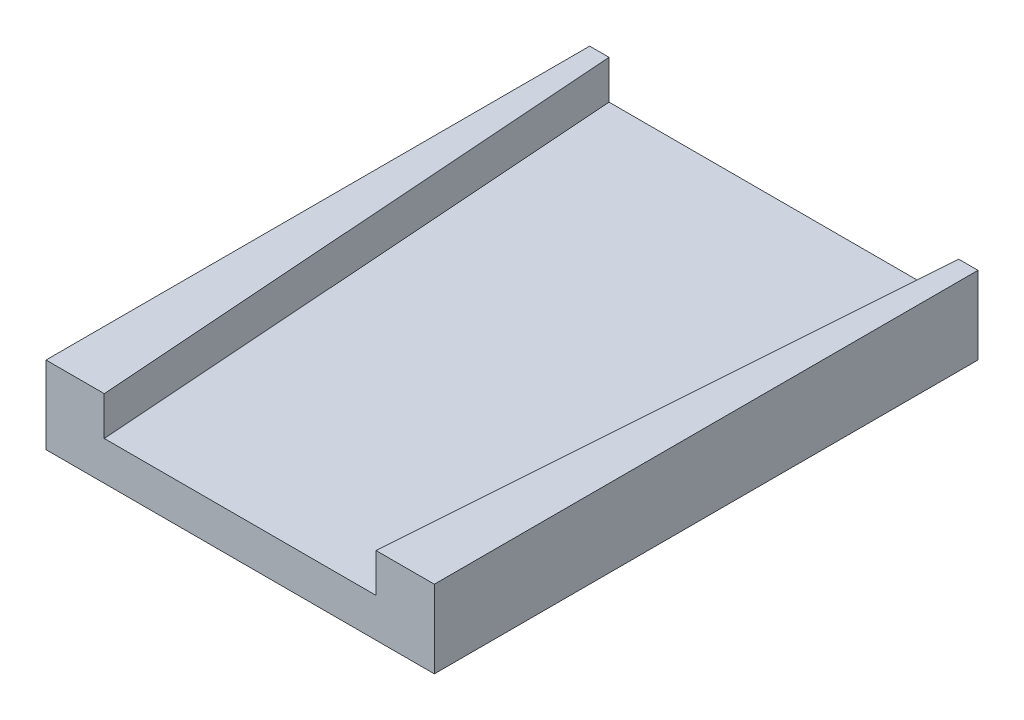
SolidWorks part; units mm, degrees
ref_plane "Front Plane" through (0, 0, 0) normal (0, 0, 1) x (1, 0, 0)
ref_plane "Top Plane" through (0, 0, 0) normal (0, 1, 0) x (1, 0, 0)
ref_plane "Right Plane" through (0, 0, 0) normal (1, 0, 0) x (0, 0, -1)
sketch "Sketch1" plane through (0, 0, 0) normal (0, 1, 0) x (1, 0, 0)
  line L1 (-63.5, -88.9) -> (63.5, -88.9)
  line L2 (-63.5, -88.9) -> (-63.5, 88.9)
  line L3 (-63.5, 88.9) -> (63.5, 88.9)
  line L4 (63.5, -88.9) -> (63.5, 88.9)
  line L5 (-63.5, -88.9) -> (63.5, 88.9) construction
  line L6 (-63.5, 88.9) -> (63.5, -88.9) construction
  point P0 (0, 0)
  dimension "D1" = 127
  dimension "D2" = 177.8
extrude "Boss-Extrude1" add sketch "Sketch1" along normal blind 25.4
sketch "Sketch2" plane through (0, 25.4, 0) normal (0, 1, 0) x (1, 0, 0)
  line L0 (-57.15, 88.9) -> (57.15, 88.9)
  line L1 (63.5, 88.9) -> (-63.5, 88.9) construction
  line L2 (57.15, 88.9) -> (44.45, -88.9)
  line L3 (-63.5, -88.9) -> (63.5, -88.9) construction
  line L4 (44.45, -88.9) -> (-44.45, -88.9)
  line L5 (-44.45, -88.9) -> (-57.15, 88.9)
  line L6 (0, 0) -> (0, -88.9) construction
  line L7 (0, 0) -> (0, 88.9) construction
  dimension "D1" = 114.3
  dimension "D2" = 88.9
extrude "Cut-Extrude2" cut sketch "Sketch2" against normal blind 12.7
